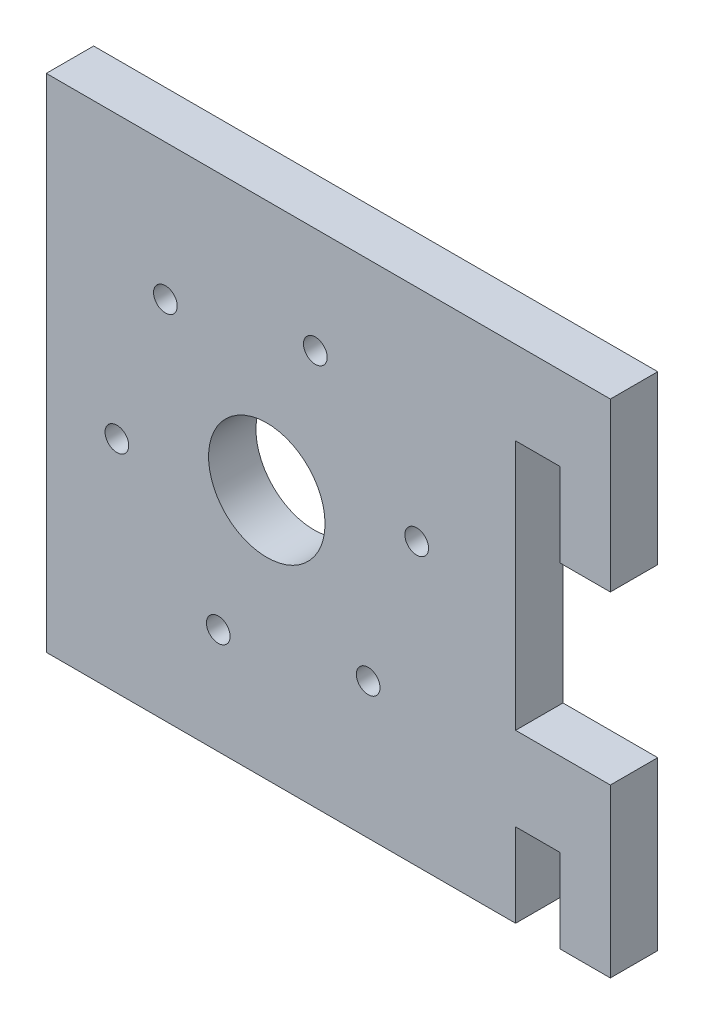
SolidWorks part; units mm, degrees
ref_plane "Front Plane" through (0, 0, 0) normal (0, 0, 1) x (1, 0, 0)
ref_plane "Top Plane" through (0, 0, 0) normal (0, 1, 0) x (1, 0, 0)
ref_plane "Right Plane" through (0, 0, 0) normal (1, 0, 0) x (0, 0, -1)
sketch "Sketch1" plane through (0, 0, 0) normal (0, 0, 1) x (1, 0, 0)
  line L1 (0, 0) -> (57.15, 0)
  line L2 (0, 0) -> (0, 50.8)
  line L3 (0, 50.8) -> (57.15, 50.8)
  line L4 (57.15, 0) -> (57.15, 50.8)
  dimension "D1" = 50.8
  dimension "D2" = 57.15
extrude "Boss-Extrude1" add sketch "Sketch1" along normal blind 4.8
sketch "Sketch5" plane through (0, 0, 4.8) normal (0, 0, 1) x (1, 0, 0)
  line L0 (57.15, 0) -> (57.15, 50.8) construction
  line L1 (57.15, 16.9333) -> (47.55, 16.9333)
  line L2 (57.15, 16.9333) -> (57.15, 33.8667)
  line L3 (57.15, 33.8667) -> (47.55, 33.8667)
  line L4 (47.55, 16.9333) -> (47.55, 33.8667)
  line L5 (57.15, 16.9333) -> (47.55, 33.8667)
  line L6 (57.15, 33.8667) -> (47.55, 16.9333)
  line L7 (57.15, 33.8667) -> (57.15, 50.8) construction
  line L8 (57.15, 16.9333) -> (57.15, 0) construction
  point P4 (52.35, 25.4)
  dimension "D1" = 9.6
  dimension "D2" = 16.9333
extrude "Cut-Extrude4" cut sketch "Sketch5" against normal through all contours L6 L5 L4
extrude "Cut-Extrude6" cut sketch "Sketch7" against normal through all contours A1
sketch "Sketch7" plane through (60.3425, 78.7742, 4.8) normal (0, 0, 1) x (0, 1, 0)
  line L16 (-36.4409, 12.7925) -> (-36.4409, 8.2925)
  line L23 (-36.4409, 8.2925) -> (-44.9076, 8.2925)
  line L28 (-61.8409, 12.7925) -> (-36.4409, 12.7925)
  line L31 (-44.9076, 8.2925) -> (-44.9076, 3.1925)
  line L32 (-44.9076, 3.1925) -> (-27.9742, 3.1925)
  line L33 (-27.9742, 3.1925) -> (-27.9742, 60.3425)
  line L34 (-27.9742, 60.3425) -> (-78.7742, 60.3425)
  line L35 (-78.7742, 60.3425) -> (-78.7742, 12.7925)
  line L39 (-78.7742, 8.2925) -> (-78.7742, 3.1925)
  line L40 (-78.7742, 3.1925) -> (-61.8409, 3.1925)
  line L41 (-61.8409, 3.1925) -> (-61.8409, 12.7925)
  line L42 (-78.7742, 12.7925) -> (-70.3076, 12.7925)
  line L44 (-70.3076, 12.7925) -> (-70.3076, 8.2925)
  line L46 (-70.3076, 8.2925) -> (-78.7742, 8.2925)
  circle A1 centre (-53.3742, 38.0001) radius 5.9
extrude "Cut-Extrude9" cut sketch "Sketch10" against normal through all contours A11 | A7 | A8 | A6 | A9 | A10
sketch "Sketch10" plane through (60.3425, 78.7742, 4.8) normal (0, 0, 1) x (0, 1, 0)
  line L16 (-36.4409, 12.7925) -> (-36.4409, 8.2925)
  line L23 (-36.4409, 8.2925) -> (-44.9076, 8.2925)
  line L28 (-61.8409, 12.7925) -> (-36.4409, 12.7925)
  line L31 (-44.9076, 8.2925) -> (-44.9076, 3.1925)
  line L32 (-44.9076, 3.1925) -> (-27.9742, 3.1925)
  line L33 (-27.9742, 3.1925) -> (-27.9742, 60.3425)
  line L34 (-27.9742, 60.3425) -> (-78.7742, 60.3425)
  line L35 (-78.7742, 60.3425) -> (-78.7742, 12.7925)
  line L39 (-78.7742, 8.2925) -> (-78.7742, 3.1925)
  line L40 (-78.7742, 3.1925) -> (-61.8409, 3.1925)
  line L41 (-61.8409, 3.1925) -> (-61.8409, 12.7925)
  line L42 (-78.7742, 12.7925) -> (-70.3076, 12.7925)
  line L44 (-70.3076, 12.7925) -> (-70.3076, 8.2925)
  line L46 (-70.3076, 8.2925) -> (-78.7742, 8.2925)
  circle A6 centre (-64.9818, 27.728) radius 1.2
  circle A7 centre (-56.4663, 53.1885) radius 1.2
  circle A8 centre (-68.0738, 42.9165) radius 1.2
  circle A9 centre (-50.2822, 22.8116) radius 1.2
  circle A10 centre (-38.6746, 33.0836) radius 1.2
  circle A11 centre (-41.7667, 48.2721) radius 1.2
sketch "Sketch11" plane through (0, 0, 4.8) normal (0, 0, 1) x (1, 0, 0)
  line L0 (47.55, 16.9333) -> (47.55, 0) construction
  line L1 (0, 0) -> (57.15, 0) construction
  line L3 (47.55, 0) -> (52.05, 0)
  line L4 (47.55, 0) -> (47.55, 8.4667)
  line L5 (47.55, 8.4667) -> (52.05, 8.4667)
  line L6 (52.05, 0) -> (52.05, 8.4667)
  line L7 (47.55, 0) -> (52.05, 8.4667) construction
  line L8 (47.55, 8.4667) -> (52.05, 0) construction
  point P8 (49.8, 4.2333)
  dimension "D1" = 4.5
  dimension "D2" = 8.4667
extrude "Cut-Extrude10" cut sketch "Sketch11" against normal through all contours L4 L3 L6 L5
sketch "Sketch12" plane through (0, 0, 4.8) normal (0, 0, 1) x (1, 0, 0)
  line L0 (47.55, 33.8667) -> (47.55, 50.8) construction
  line L2 (57.15, 50.8) -> (0, 50.8) construction
  line L3 (47.55, 33.8667) -> (52.05, 33.8667)
  line L4 (47.55, 33.8667) -> (47.55, 42.3333)
  line L5 (47.55, 42.3333) -> (52.05, 42.3333)
  line L6 (52.05, 33.8667) -> (52.05, 42.3333)
  line L7 (47.55, 33.8667) -> (52.05, 42.3333)
  line L8 (47.55, 42.3333) -> (52.05, 33.8667)
  point P8 (49.8, 38.1)
  line M22 (47.55, 33.8667) -> (57.15, 33.8667)
  dimension "D1" = 4.5
  dimension "D2" = 8.4667
extrude "Cut-Extrude11" cut sketch "Sketch12" against normal through all contours L8 L7 M22 | L8 L4 L7
extrude "Cut-Extrude20" cut sketch "Sketch21" against normal through all
sketch "Sketch21" plane through (60.6425, 75.62, 60.6866) normal (0, 0, 1) x (0.8371, 0.5471, 0)
  line L16 (-48.5036, -58.5074) -> (-44.2345, -61.2975)
  line L26 (-44.2345, -61.2975) -> (-34.9705, -47.123)
  line L32 (-25.7064, -32.9486) -> (-16.4424, -18.7741)
  line L33 (-16.4424, -18.7741) -> (-64.2813, 12.492)
  line L34 (-64.2813, 12.492) -> (-92.0733, -30.0315)
  line L35 (-92.0733, -30.0315) -> (-52.2704, -56.0455)
  line L42 (-25.3435, -23.0712) -> (-29.9755, -30.1584)
  line L50 (-52.2704, -56.0455) -> (-47.6982, -49.0497)
  line L52 (-34.9705, -47.123) -> (-43.0064, -41.871)
  line L57 (-29.1104, -20.6093) -> (-25.3435, -23.0712)
  line L58 (-43.0064, -41.871) -> (-29.1104, -20.6093)
  line L60 (-29.9755, -30.1584) -> (-25.7064, -32.9486)
  line L62 (-47.6982, -49.0497) -> (-43.9313, -51.5116)
  line L64 (-43.9313, -51.5116) -> (-48.5036, -58.5074)
  circle A1 centre (-59.2837, -21.2486) radius 17.8492
extrude "Cut-Extrude21" cut sketch "Sketch22" against normal through all
sketch "Sketch22" plane through (60.3425, 75.62, -56.4866) normal (0, 0, -1) x (0, -1, 0)
  line L16 (41.7534, 8.5925) -> (33.2867, 8.5925)
  line L22 (75.62, 3.4925) -> (75.62, 8.5925)
  line L23 (33.2867, 8.5925) -> (33.2867, 13.0925)
  line L25 (41.7534, 3.4925) -> (41.7534, 8.5925)
  line L27 (33.2867, 13.0925) -> (58.6867, 13.0925)
  line L32 (75.62, 13.0925) -> (75.62, 60.6425)
  line L33 (75.62, 60.6425) -> (24.82, 60.6425)
  line L34 (24.82, 60.6425) -> (24.82, 3.4925)
  line L35 (24.82, 3.4925) -> (41.7534, 3.4925)
  line L46 (67.2626, 13.0925) -> (75.62, 13.0925)
  line L47 (58.6867, 13.0925) -> (58.6867, 3.4925)
  line L49 (58.6867, 3.4925) -> (75.62, 3.4925)
  line L51 (75.62, 8.5925) -> (67.2626, 8.5925)
  line L53 (67.2626, 8.5925) -> (67.2626, 13.0925)
  circle A2 centre (50.22, 38.0001) radius 17.8492
equation "\"MDF\"= 4.8mm"
equation "\"Foamcore\"= 4.6mm"
equation "\"GMaterial\"= \"MDF\""
equation "\"D1@Boss-Extrude1\"=\"GMaterial\""
equation "\"PCB\" = 1.6mm"
equation "\"BaseWidth\" = 10in"
equation "\"SkidLength\" = 1in"
equation "\"SkidClearance\" = 0.4in"
equation "\"MotorMountLength\" = 2in"
equation "\"MotorMountWidth\" = \"GMaterial\""
equation "\"MotorMountHeight\" = 2.25in"
equation "\"D1@Sketch1\"=\"MotorMountLength\""
equation "\"MotorShoulderRadius\"=0.464567"
equation "\"OutterMotorMountHeight\"=2.25"
equation "\"D2@Sketch1\"=\"OutterMotorMountHeight\""
equation "\"D1@Sketch5\"=\"GMaterial\"*2"
equation "\"UnoStackWidth\" = 77.4mm"
equation "\"UnoStackLength\" = 79.8mm"
equation "\"UnoStackHeight\" = 34.2mm"
equation "\"TallHexRiserHeight\" = 22.2mm"
equation "\"PingPongBallSize\" = 40mm"
equation "\"BarrelLength\" = 9in"
equation "\"BarrelSize\" = \"PingPongBallSize\""
equation "\"PlatformLength\" = 4in"
equation "\"PlatformWidth\" = 6in"
equation "\"WheelWidth\"= 26mm"
equation "\"WheelDiameter\"=2.99213"
equation "\"ServoMountHeight\"=2.49223"
equation "\"ServoGearHeight\" = 0.95330261in"
equation "\"ServoMountLength\"= 1.53774"
equation "\"PivotHoleRadius\"= 0.616358"
equation "\"PlatformMountHeight\" = 3.19"
equation "\"TensionOffSet\"= .3mm"
equation "\"MotorMountWedge\"=0.333333"
equation "\"LaserCutterOffset\"= .3mm"
equation "\"D1@Sketch11\"=\"GMaterial\"-\"LaserCutterOffset\""
equation "\"D1@Sketch12\"=\"GMaterial\"-\"LaserCutterOffset\""
